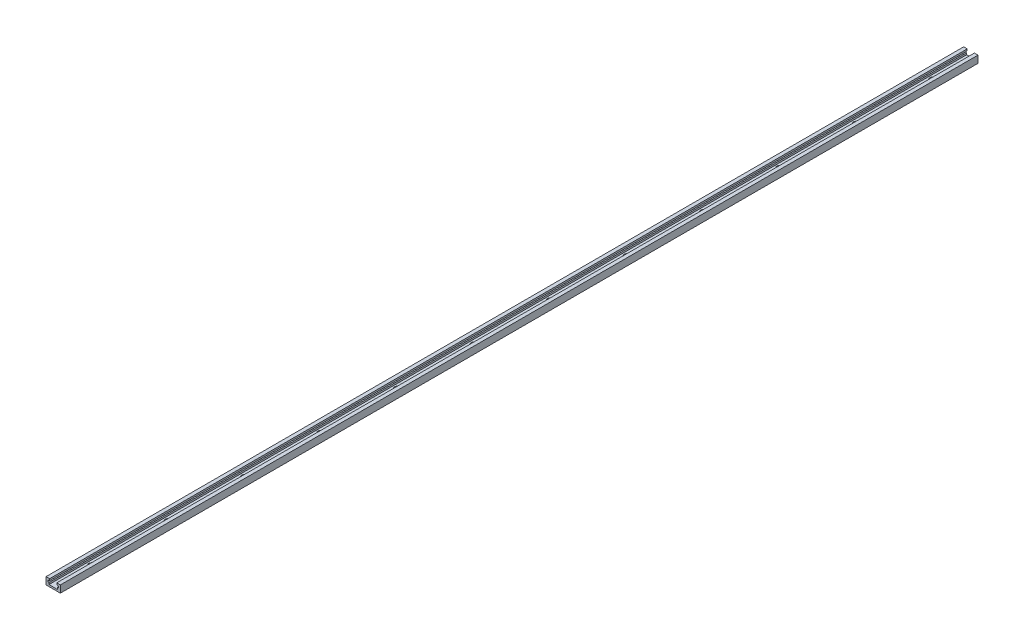
SolidWorks part; units mm, degrees
material "6061 Alloy"
ref_plane "Front Plane" through (0, 0, 0) normal (0, 0, 1) x (1, 0, 0)
ref_plane "Top Plane" through (0, 0, 0) normal (0, 1, 0) x (1, 0, 0)
ref_plane "Right Plane" through (0, 0, 0) normal (1, 0, 0) x (0, 0, -1)
sketch "Sketch1" plane through (0, 0, 0) normal (0, 0, 1) x (1, 0, 0)
  line L0 (0, 0) -> (0, -77.2163) construction
  line L1 (-4.7625, 0) -> (-9.525, 0)
  line L2 (4.7625, 0) -> (9.525, 0)
  line L3 (-9.525, 0) -> (-9.525, -9.525)
  line L4 (9.525, 0) -> (9.525, -9.525)
  line L5 (-9.525, -9.525) -> (9.525, -9.525)
  line L6 (-4.7625, 0) -> (-4.7625, -2.3812)
  line L7 (4.7625, 0) -> (4.7625, -2.3812)
  line L8 (-4.7625, -2.3812) -> (-7.1438, -2.3813)
  line L9 (4.7625, -2.3812) -> (7.1438, -2.3812)
  line L10 (-7.1438, -2.3813) -> (-7.1438, -4.7625)
  line L11 (7.1438, -2.3812) -> (7.1438, -4.7625)
  line L12 (-7.1438, -4.7625) -> (-5.5562, -4.7625)
  line L13 (7.1438, -4.7625) -> (5.5563, -4.7625)
  line L14 (5.5563, -4.7625) -> (5.5563, -7.1437)
  line L15 (-5.5562, -4.7625) -> (-5.5562, -7.1437)
  line L16 (5.5563, -7.1437) -> (-5.5562, -7.1437)
  point P9 (0, -9.525)
  point P20 (0, -7.1437)
  dimension "D1" = 9.525
  dimension "D2" = 2.3813
  dimension "D3" = 2.3813
  dimension "D4" = 14.2875
  dimension "D5" = 11.1125
  dimension "D6" = 7.1437
  dimension "D7" = 19.05
  dimension "D8" = 9.525
extrude "Boss-Extrude1" add sketch "Sketch1" along normal mid plane 1219.2
sketch "Sketch2" [suppressed] plane through (0, 0, 0) normal (0, 1, 0) x (1, 0, 0)
  line L0 (9.525, -288.925) -> (0, -279.4)
  line L1 (9.525, -355.6) -> (9.525, 355.6) construction
  line L2 (0, -279.4) -> (-9.525, -288.925)
  line L3 (-9.525, -355.6) -> (-9.525, 355.6) construction
  line L4 (-9.525, -288.925) -> (-9.525, 355.6)
  line L5 (-9.525, 355.6) -> (9.525, 355.6)
  line L6 (9.525, 355.6) -> (9.525, -288.925)
  line L7 (5.5563, -355.6) -> (-5.5562, -355.6) construction
  dimension "D1" = 76.2
  dimension "D2" = 90
extrude "Cut-Extrude1" [suppressed] cut sketch "Sketch2" against normal up to surface (9.525 mm away)
hole_wizard "CSK for #6 Flat Head Machine Screw1" [suppressed] positions "Sketch5" profile "Sketch4" countersink size "#6" standard "ANSI Inch"
sketch "Sketch5" plane through (0, -7.1437, 0) normal (0, 1, 0) x (1, 0, 0)
  line L0 (0, -457.2) -> (0, -381) construction
  line L1 (5.5563, -457.2) -> (-5.5563, -457.2) construction
  point P8 (0, -444.5)
  point P10 (0, -400.05)
  dimension "D1" = 44.45
  dimension "D2" = 12.7
sketch "Sketch4" plane through (0, -7.1437, 444.5) normal (1, 0, 0) x (0, 0, 1)
  line L0 (0, 0) -> (0, 2.3813)
  line L1 (0, 2.3813) -> (1.8986, 2.3813)
  line L2 (1.8986, 2.3813) -> (1.8986, 1.892)
  line L3 (1.8986, 1.892) -> (3.5433, 0)
  line L5 (3.5433, 0) -> (0, 0)
  line L6 (-1.8986, 1.892) -> (-3.5433, 0) construction
  line L11 (0, -6.35) -> (0, 107.95) construction
  dimension "Thru Hole Dia." = 3.7973
  dimension "Thru Hole Depth" = 2.3813
  dimension "Near C'Sink Dia." = 7.0866
  dimension "Near C'Sink Angle" = 82
sketch "Sketch6" [suppressed] plane through (9.525, 0, 0) normal (1, 0, 0) x (0, 0, -1)
  line L0 (-355.6, 0) -> (355.6, 0) construction
  line L1 (-327.025, 0) -> (-314.325, 0)
  line L2 (-327.025, 0) -> (-327.025, -7.1437)
  line L3 (-327.025, -7.1437) -> (-314.325, -7.1437)
  line L4 (-314.325, 0) -> (-314.325, -7.1437)
  line L5 (-355.6, -9.525) -> (-355.6, 0) construction
  line L6 (-355.6, -9.525) -> (355.6, -9.525) construction
  line L8 (-35.7187, 0) -> (-23.0187, 0)
  line L9 (-35.7187, 0) -> (-35.7187, -7.1437)
  line L10 (-35.7187, -7.1437) -> (-23.0187, -7.1437)
  line L11 (-23.0187, 0) -> (-23.0187, -7.1437)
  line L12 (313.5312, 0) -> (326.2312, 0)
  line L13 (313.5312, 0) -> (313.5313, -7.1437)
  line L14 (313.5313, -7.1437) -> (326.2312, -7.1437)
  line L15 (326.2312, 0) -> (326.2312, -7.1437)
  dimension "D1" = 28.575
  dimension "D2" = 12.7
  dimension "D3" = 2.3813
  dimension "D4" = 278.6062
  dimension "D5" = 336.55
extrude "Cut-Extrude2" [suppressed] cut sketch "Sketch6" against normal through all
hole_wizard "CSK for #6 Flat Head Machine Screw2" positions "Sketch8" profile "Sketch7" countersink size "#6" standard "ANSI Inch" end condition through all
sketch "Sketch8" plane through (0, -7.1437, 0) normal (0, 1, 0) x (1, 0, 0)
  line L0 (0, 609.6) -> (0, 568.6796) construction
  line L1 (5.5563, 609.6) -> (-5.5563, 609.6) construction
  point P7 (0, 558.8)
  dimension "D1" = 50.8
sketch "Sketch7" plane through (0, -7.1437, -558.8) normal (1, 0, 0) x (0, 0, 1)
  line L0 (0, 0) -> (0, 2.3813)
  line L1 (0, 2.3813) -> (1.8986, 2.3813)
  line L2 (1.8986, 2.3813) -> (1.8986, 1.892)
  line L3 (1.8986, 1.892) -> (3.5433, 0)
  line L5 (3.5433, 0) -> (0, 0)
  line L6 (-1.8986, 1.892) -> (-3.5433, 0) construction
  line L11 (0, -6.35) -> (0, 107.95) construction
  dimension "Thru Hole Dia." = 3.7973
  dimension "Thru Hole Depth" = 2.3813
  dimension "Near C'Sink Dia." = 7.0866
  dimension "Near C'Sink Angle" = 82
pattern_linear "LPattern1" count 12 spacing 101.6 along (0, 0, 1) of "CSK for #6 Flat Head Machine Screw2"
